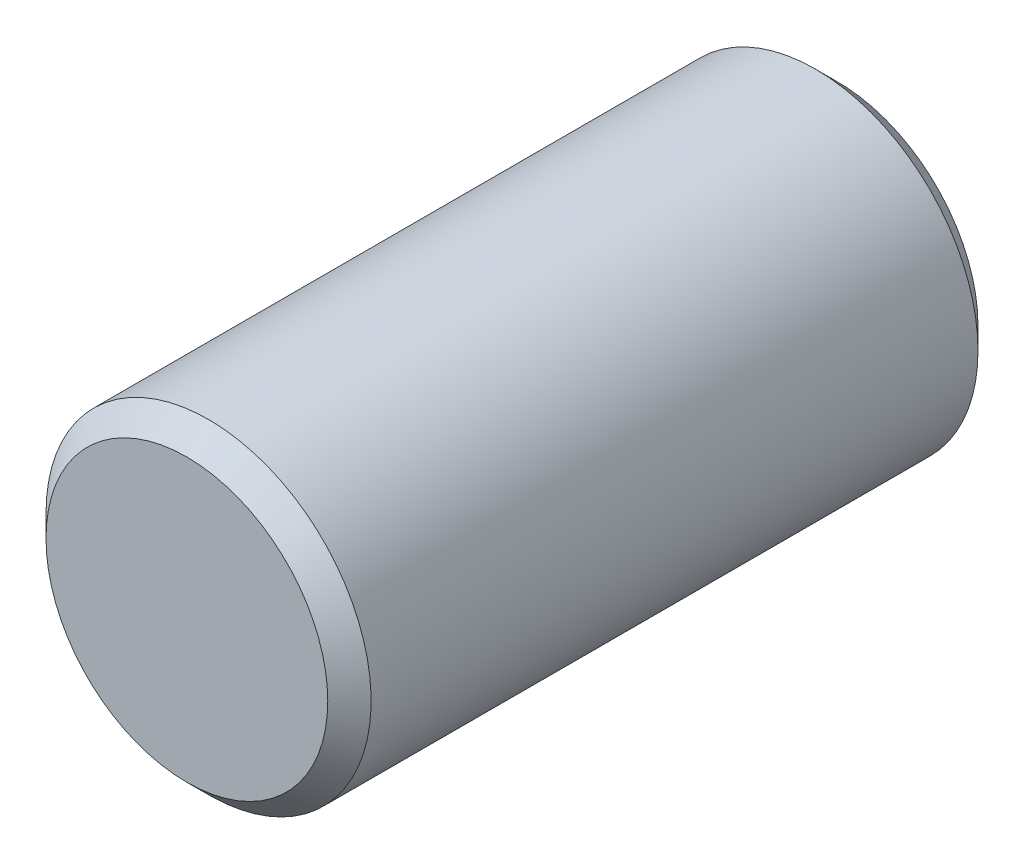
SolidWorks part; units mm, degrees
ref_plane "Front Plane" through (0, 0, 0) normal (0, 0, 1) x (1, 0, 0)
ref_plane "Top Plane" through (0, 0, 0) normal (0, 1, 0) x (1, 0, 0)
ref_plane "Right Plane" through (0, 0, 0) normal (1, 0, 0) x (0, 0, -1)
sketch "Sketch1" plane through (0, 0, 0) normal (0, 0, 1) x (1, 0, 0)
  circle A0 centre (0, 0) radius 9.525
  dimension "D1" = 19.05
extrude "Boss-Extrude1" add sketch "Sketch1" along normal blind 38.1
chamfer "Chamfer1" distance 1.27 angle 45 2 edges at (9.525, 0, 0) (9.525, 0, 38.1)
